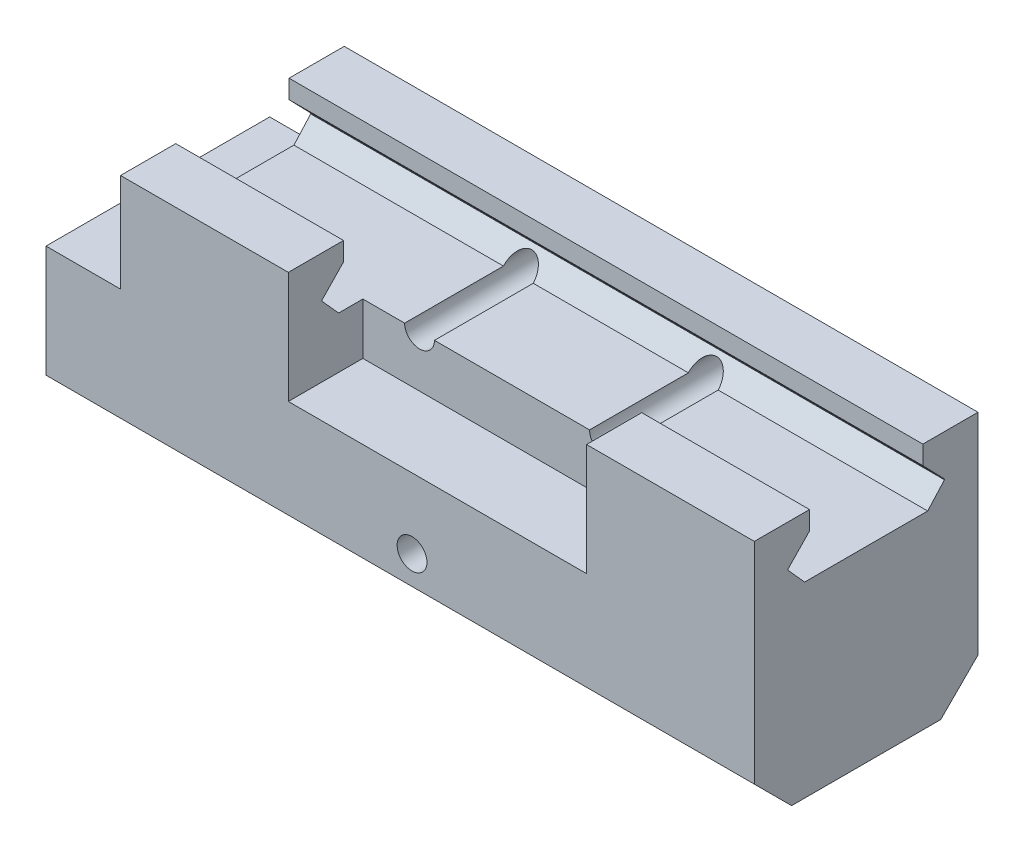
SolidWorks part; units mm, degrees
ref_plane "정면" through (0, 0, 0) normal (0, 0, 1) x (1, 0, 0)
ref_plane "윗면" through (0, 0, 0) normal (0, 1, 0) x (1, 0, 0)
ref_plane "우측면" through (0, 0, 0) normal (1, 0, 0) x (0, 0, -1)
sketch "스케치1" plane through (0, 0, 0) normal (1, 0, 0) x (0, 0, -1)
  line L1 (-15, 10) -> (15, 10)
  line L2 (-15, 10) -> (-15, -10)
  line L3 (-15, -10) -> (15, -10)
  line L4 (15, 10) -> (15, -10)
  line L5 (-15, 10) -> (15, -10) construction
  line L6 (-15, -10) -> (15, 10) construction
  line L7 (-6, 5) -> (6, 5)
  line L8 (-6, 5) -> (-6, -5)
  line L9 (-6, -5) -> (6, -5)
  line L10 (6, 5) -> (6, -5)
  line L11 (-6, 5) -> (6, -5) construction
  line L12 (-6, -5) -> (6, 5) construction
  point P0 (0, 0)
  point P6 (0, 0)
  dimension "D1" = 30
  dimension "D2" = 20
  dimension "D3" = 12
  dimension "D4" = 10
extrude "보스-돌출1" add sketch "스케치1" along normal blind 10
sketch "스케치2" plane through (0, 0, -15) normal (0, 0, -1) x (-1, 0, 0)
  line L1 (-1.175, -2.0063) -> (-1.175, 2.0063)
  line L2 (-1.175, 2.0063) -> (-4.65, 4.0126)
  line L3 (-4.65, 4.0126) -> (-8.125, 2.0063)
  line L4 (-8.125, 2.0063) -> (-8.125, -2.0063)
  line L5 (-8.125, -2.0063) -> (-4.65, -4.0126)
  line L6 (-4.65, -4.0126) -> (-1.175, -2.0063)
  line L7 (0, -10) -> (0, 10) construction
  circle A0 centre (-4.65, 0) radius 3.475 construction
  dimension "D1" = 6.95
  dimension "D2" = 4.65
extrude "컷-돌출1" cut sketch "스케치2" against normal blind 3
sketch "스케치4" plane through (0, 0, 0) normal (0, 0, 1) x (1, 0, 0)
  line L0 (0, 0) -> (4.65, 0) construction
  line L1 (4.65, 0) -> (4.65, 10) construction
  circle A0 centre (4.65, 0) radius 1.95
  dimension "D1" = 3.9
  dimension "D2" = 4.65
extrude "컷-돌출2" cut sketch "스케치4" against normal blind 30
sketch "스케치8" plane through (0, 0, 6) normal (0, 0, -1) x (-1, 0, 0)
  circle A0 centre (-4.65, 0) radius 2.8
  circle A1 centre (-4.65, 0) radius 2.2
  dimension "D1" = 5.6
  dimension "D2" = 4.4
extrude "컷-돌출3" cut sketch "스케치8" against normal blind 5
fillet "필렛1" radius 1 1 edges at (4.65, 2.2, 6)
sketch "스케치12" plane through (0, 0, 0) normal (0, 0, 1) x (1, 0, 0)
  line L1 (10, 23.2) -> (95, 23.2)
  line L2 (10, 23.2) -> (10, -10)
  line L3 (10, -10) -> (95, -10)
  line L4 (95, 23.2) -> (95, -10)
  dimension "D1" = 85
  dimension "D2" = 33.2
extrude "보스-돌출3" add sketch "스케치12" along normal mid plane 30
sketch "스케치13" plane through (0, 0, 0) normal (1, 0, 0) x (0, 0, -1)
  line L0 (0, 0) -> (0, 23.2) construction
  line L1 (-15, 23.2) -> (15, 23.2) construction
  line L2 (7.6, 23.2) -> (-7.6, 23.2)
  line L3 (-7.6, 23.2) -> (-7.6, 20.7)
  line L4 (-10.5, 17.7) -> (-10.5, 17.6)
  line L5 (-10.5, 17.6) -> (-8.25, 15.1)
  line L6 (-8.25, 15.1) -> (8.25, 15.1)
  line L7 (-7.6, 20.7) -> (-10.5, 17.7)
  line L8 (7.6, 20.7) -> (10.5, 17.7)
  line L9 (10.5, 17.6) -> (8.25, 15.1)
  line L10 (10.5, 17.7) -> (10.5, 17.6)
  line L11 (7.6, 23.2) -> (7.6, 20.7)
  point P14 (0, 15.1)
  dimension "D1" = 15.2
  dimension "D2" = 16.5
  dimension "D3" = 21
  dimension "D4" = 0.1
  dimension "D5" = 3
  dimension "D6" = 2.5
  dimension "D7" = 2.5
extrude "컷-돌출4" cut sketch "스케치13" along normal mid plane 200
chamfer "모따기1" distance 5 angle 45 2 edges at (47.5, -10, 15) (47.5, -10, -15)
sketch "스케치14" plane through (0, 0, 0) normal (0, 0, 1) x (1, 0, 0)
  line L1 (40.1, 15.1) -> (64.9, 15.1) construction
  line L2 (52.5, 23.2) -> (52.5, 15.1) construction
  line L3 (95, 23.2) -> (10, 23.2) construction
  line L4 (95, 15.1) -> (10, 15.1) construction
  circle A0 centre (40.1, 15.1) radius 2
  circle A1 centre (64.9, 15.1) radius 2
  dimension "D1" = 4
  dimension "D2" = 4
  dimension "D3" = 24.8
extrude "컷-돌출5" cut sketch "스케치14" against normal through all both and the other way through all
sketch "스케치15" plane through (0, 0, 0) normal (0, 0, 1) x (1, 0, 0)
  line L0 (62.7132, 5.725) -> (49.0927, 5.725)
  line L1 (42.1726, -1.1951) -> (42.1726, -12.6287)
  line L2 (42.1726, -12.6287) -> (87.3179, -12.6287)
  line L3 (87.3179, -12.6287) -> (87.3179, -10)
  line L4 (87.3179, -10) -> (62.7132, 5.725)
  line L5 (95, -10) -> (0, -10) construction
  arc A0 (49.0927, 5.725) -> (42.1726, -1.1951) centre (49.0927, -1.1951) ccw
extrude "컷-돌출6" cut sketch "스케치15" against normal mid plane 15
sketch "스케치16" plane through (0, 0, 0) normal (0, 0, 1) x (1, 0, 0)
  circle A0 centre (49.0927, -1.1951) radius 2
  dimension "D1" = 4
extrude "컷-돌출7" cut sketch "스케치16" against normal through all both and the other way through all
sketch "스케치17" plane through (0, 0, 15) normal (0, 0, 1) x (1, 0, 0)
  line L0 (52.5, 23.2) -> (52.5, 8.2) construction
  line L1 (95, 23.2) -> (10, 23.2) construction
  line L2 (72.5, 8.2) -> (32.5, 8.2)
  line L3 (32.5, 8.2) -> (32.5, 23.2)
  line L4 (32.5, 23.2) -> (72.5, 23.2)
  line L5 (72.5, 8.2) -> (72.5, 23.2)
  dimension "D1" = 15
  dimension "D2" = 40
extrude "컷-돌출8" cut sketch "스케치17" against normal blind 10
